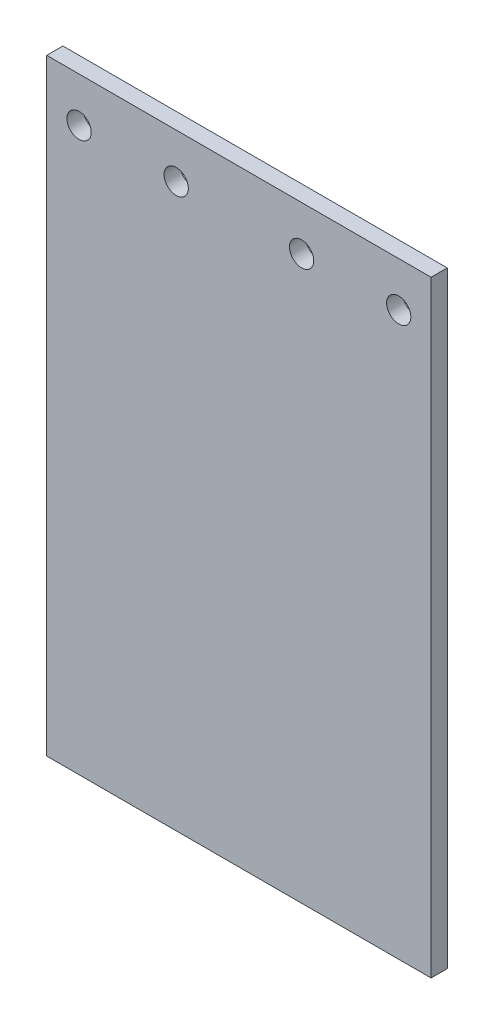
SolidWorks part; units mm, degrees
ref_plane "Front" through (0, 0, 0) normal (0, 0, 1) x (1, 0, 0)
ref_plane "Top" through (0, 0, 0) normal (0, 1, 0) x (1, 0, 0)
ref_plane "Right" through (0, 0, 0) normal (1, 0, 0) x (0, 0, -1)
sketch "草图1" plane through (0, 0, 0) normal (0, 0, 1) x (1, 0, 0)
  line L1 (-47.5, -75) -> (47.5, -75)
  line L2 (-47.5, -75) -> (-47.5, 75)
  line L3 (-47.5, 75) -> (47.5, 75)
  line L4 (47.5, -75) -> (47.5, 75)
  line L5 (-47.5, -75) -> (47.5, 75) construction
  line L6 (-47.5, 75) -> (47.5, -75) construction
  point P0 (0, 0)
  dimension "D1" = 95
  dimension "D2" = 150
extrude "凸台-拉伸1" add sketch "草图1" along normal blind 4
sketch "草图2" plane through (0, 0, 4) normal (0, 0, 1) x (1, 0, 0)
  line L0 (47.5, 75) -> (-47.5, 75) construction
  line L1 (-47.5, 75) -> (-47.5, -75) construction
  circle A0 centre (-39.5, 64) radius 3
  circle A1 centre (-15.5, 64) radius 3
  dimension "D4" = 6
  dimension "D1" = 24
  dimension "D2" = 11
  dimension "D3" = 8
extrude "切除-拉伸1" cut sketch "草图2" against normal through all
mirror "镜向1" about plane through (0, 0, 0) normal (1, 0, 0) of "切除-拉伸1"
